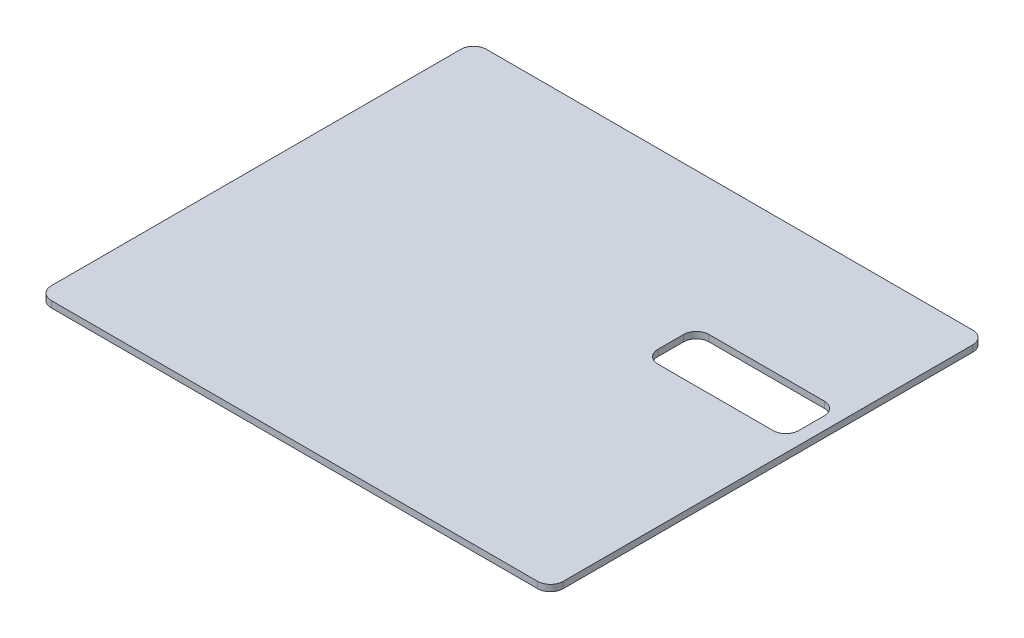
SolidWorks part; units mm, degrees
material "PC High Viscosity"
ref_plane "Front Plane" through (0, 0, 0) normal (0, 0, 1) x (1, 0, 0)
ref_plane "Top Plane" through (0, 0, 0) normal (0, 1, 0) x (1, 0, 0)
ref_plane "Right Plane" through (0, 0, 0) normal (1, 0, 0) x (0, 0, -1)
sketch "Sketch1" plane through (0, 0, 0) normal (0, 1, 0) x (1, 0, 0)
  line L0 (254, 148.59) -> (254, 215.9)
  line L1 (0, 0) -> (254, 0)
  line L2 (0, 0) -> (0, 215.9)
  line L3 (0, 215.9) -> (254, 215.9)
  line L4 (254, 0) -> (254, 123.19)
  line L5 (247.65, 123.19) -> (177.8, 123.19)
  line L7 (247.65, 148.59) -> (177.8, 148.59)
  line L8 (177.8, 123.19) -> (177.8, 148.59)
  line L11 (254, 123.19) -> (254, 148.59)
  line L13 (247.65, 123.19) -> (247.65, 148.59)
  dimension "D1" = 254
  dimension "D2" = 215.9
  dimension "D3" = 67.31
  dimension "D4" = 25.4
  dimension "D5" = 76.2
  dimension "D6" = 6.35
extrude "Boss-Extrude1" add sketch "Sketch1" along normal blind 3.175
fillet "Fillet1" radius 6.35 8 edges at (0, 1.5875, -215.9) (254, 1.5875, -215.9) (0, 1.5875, 0) (254, 1.5875, 0) (177.8, 1.5875, -148.59) (177.8, 1.5875, -123.19) (247.65, 1.5875, -123.19) (247.65, 1.5875, -148.59)
